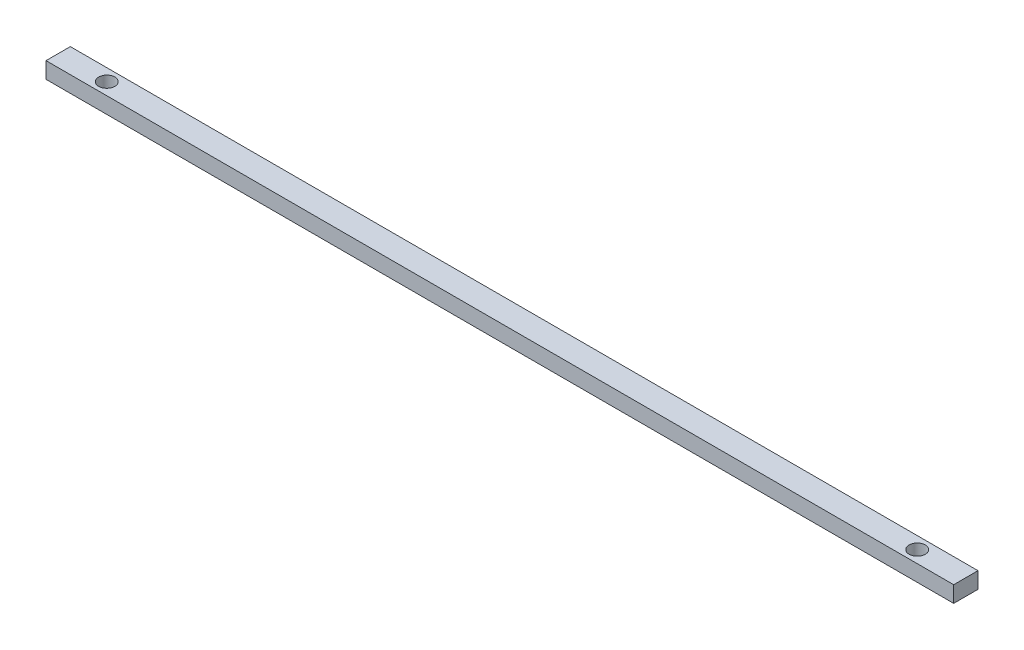
SolidWorks part; units mm, degrees
ref_plane "Front Plane" through (0, 0, 0) normal (0, 0, 1) x (1, 0, 0)
ref_plane "Top Plane" through (0, 0, 0) normal (0, 1, 0) x (1, 0, 0)
ref_plane "Right Plane" through (0, 0, 0) normal (1, 0, 0) x (0, 0, -1)
sketch "Sketch2" plane through (0, 0, 0) normal (1, 0, 0) x (0, 0, -1)
  line L1 (-7.5, 5) -> (7.5, 5)
  line L2 (-7.5, 5) -> (-7.5, -5)
  line L3 (-7.5, -5) -> (7.5, -5)
  line L4 (7.5, 5) -> (7.5, -5)
  line L5 (-7.5, 5) -> (7.5, -5) construction
  line L6 (-7.5, -5) -> (7.5, 5) construction
  point P0 (0, 0)
  dimension "D1" = 15
  dimension "D2" = 10
extrude "Boss-Extrude1" add sketch "Sketch2" along normal blind 560
sketch "Sketch3" plane through (0, 5, 0) normal (0, 1, 0) x (1, 0, 0)
  line L1 (560, -7.5) -> (0, -7.5) construction
  line L2 (0, 7.5) -> (0, -7.5) construction
  line L3 (560, 7.5) -> (560, -7.5) construction
  circle A0 centre (30, 0) radius 5
  circle A1 centre (530, 0) radius 5
  dimension "D1" = 10
  dimension "D2" = 10
  dimension "D3" = 7.5
  dimension "D4" = 30
  dimension "D5" = 30
  dimension "D6" = 7.5
extrude "Cut-Extrude1" cut sketch "Sketch3" against normal blind 10
